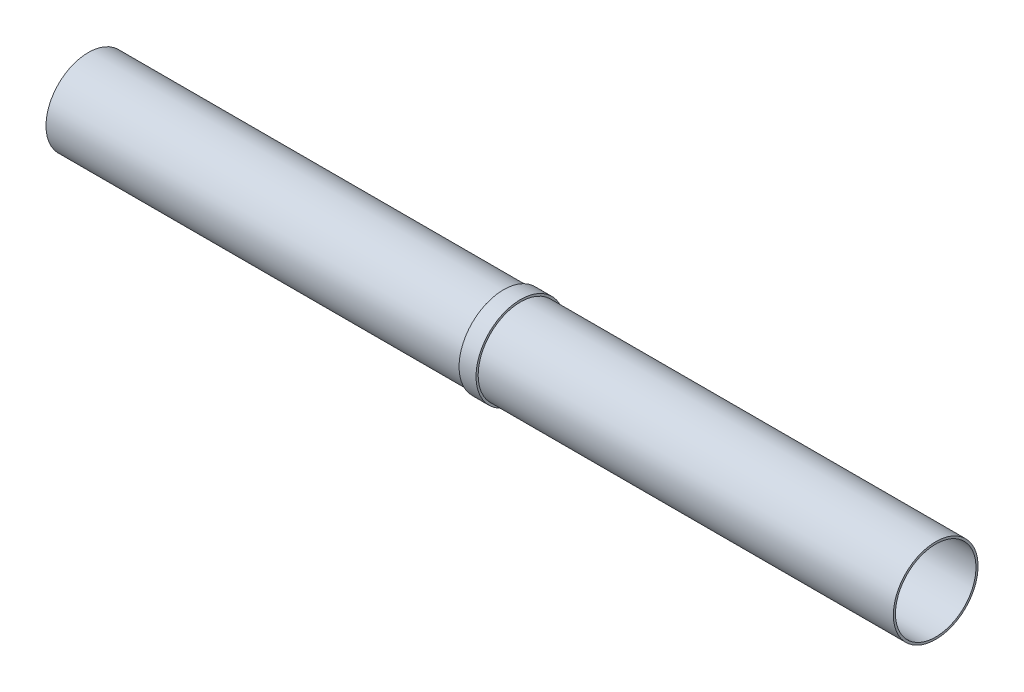
SolidWorks part; units mm, degrees
ref_plane "Front Plane" through (0, 0, 0) normal (0, 0, 1) x (1, 0, 0)
ref_plane "Top Plane" through (0, 0, 0) normal (0, 1, 0) x (1, 0, 0)
ref_plane "Right Plane" through (0, 0, 0) normal (1, 0, 0) x (0, 0, -1)
sketch "Sketch1" plane through (0, 0, 0) normal (1, 0, 0) x (0, 0, -1)
  circle A0 centre (0, 0) radius 63.5
  circle A1 centre (0, 0) radius 133.35
  circle A2 centre (0, 0) radius 60.325
extrude "Boss-Extrude1" add sketch "Sketch1" along normal mid plane 1270 contours A0 A2
sketch "Sketch3" plane through (0, 0, 0) normal (1, 0, 0) x (0, 0, -1)
  circle A0 centre (0, 0) radius 66.675
extrude "Boss-Extrude3" add sketch "Sketch3" along normal mid plane 25.4 contours A0
sketch "Sketch13" plane through (-12.7, 0, 0) normal (-1, 0, 0) x (0, 0, 1)
  circle A0 centre (0, 0) radius 60.325
extrude "Cut-Extrude2" cut sketch "Sketch13" against normal mid plane 144.78 contours A0
